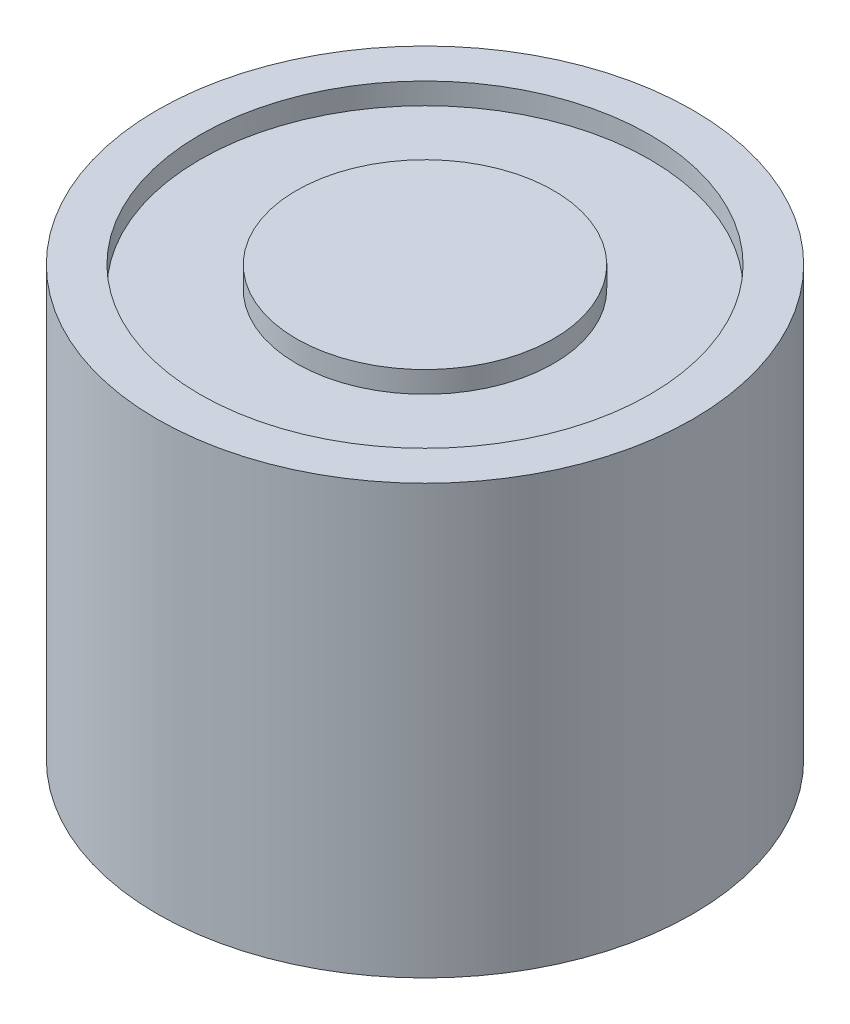
SolidWorks part; units mm, degrees
material "AISI 1020"
ref_plane "Front Plane" through (0, 0, 0) normal (0, 0, 1) x (1, 0, 0)
ref_plane "Top Plane" through (0, 0, 0) normal (0, 1, 0) x (1, 0, 0)
ref_plane "Right Plane" through (0, 0, 0) normal (1, 0, 0) x (0, 0, -1)
sketch "Sketch1" plane through (0, 0, 0) normal (0, 1, 0) x (1, 0, 0)
  circle A0 centre (0, 0) radius 12.5
  point P2 (0, 0)
  dimension "D1" = 25
extrude "Boss-Extrude1" add sketch "Sketch1" along normal blind 20
sketch "Sketch2" plane through (0, 20, 0) normal (0, 1, 0) x (1, 0, 0)
  circle A0 centre (0, 0) radius 6
  circle A1 centre (0, 0) radius 10.5
  dimension "D1" = 12
  dimension "D2" = 21
extrude "Cut-Extrude1" cut sketch "Sketch2" against normal blind 1
